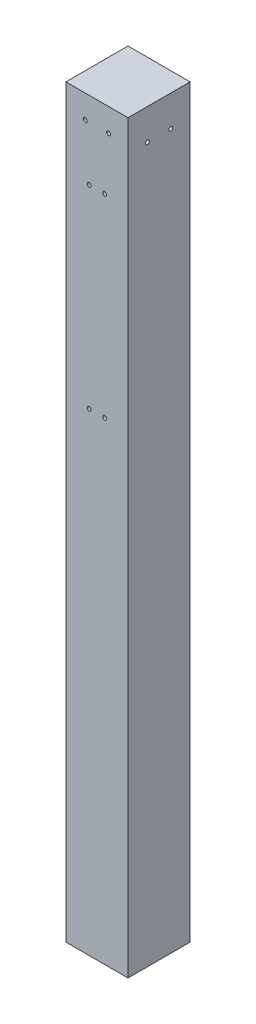
SolidWorks part; units mm, degrees
material "Pine"
ref_plane "Frontal Plane" through (0, 0, 0) normal (0, 0, 1) x (1, 0, 0)
ref_plane "Horizontal Plane" through (0, 0, 0) normal (0, 1, 0) x (1, 0, 0)
ref_plane "Profile Plane" through (0, 0, 0) normal (1, 0, 0) x (0, 0, -1)
sketch "Sketch1" plane through (0, 0, 0) normal (0, 1, 0) x (1, 0, 0)
  line L1 (50.8, -50.8) -> (-50.8, -50.8)
  line L2 (50.8, -50.8) -> (50.8, 50.8)
  line L3 (50.8, 50.8) -> (-50.8, 50.8)
  line L4 (-50.8, -50.8) -> (-50.8, 50.8)
  line L5 (50.8, -50.8) -> (-50.8, 50.8) construction
  line L6 (50.8, 50.8) -> (-50.8, -50.8) construction
  point P0 (0, 0)
  dimension "D1" = 101.6
  dimension "D2" = 101.6
extrude "Boss-Extrude1" add sketch "Sketch1" along normal mid plane 1219.2
sketch "Sketch2" plane through (50.8, 0, 0) normal (1, 0, 0) x (0, 0, -1)
  line L0 (-50.8, 609.6) -> (50.8, 609.6) construction
  line L1 (-50.8, 609.6) -> (-50.8, -609.6) construction
  line L2 (50.8, 609.6) -> (50.8, -609.6) construction
  circle A0 centre (-19.05, 558.8) radius 3.175
  circle A1 centre (19.05, 558.8) radius 3.175
  dimension "D2" = 6.35
  dimension "D1" = 50.8
  dimension "D3" = 31.75
  dimension "D4" = 31.75
extrude "Cut-Extrude1" cut sketch "Sketch2" against normal through all
sketch "Sketch3" plane through (0, 0, 50.8) normal (0, 0, 1) x (1, 0, 0)
  line L0 (-50.8, 609.6) -> (50.8, 609.6) construction
  line L1 (-50.8, 609.6) -> (-50.8, -609.6) construction
  line L2 (50.8, 609.6) -> (50.8, -609.6) construction
  circle A0 centre (-19.05, 571.5) radius 3.175
  circle A1 centre (19.05, 571.5) radius 3.175
  dimension "D1" = 6.35
  dimension "D2" = 38.1
  dimension "D3" = 31.75
  dimension "D4" = 31.75
extrude "Cut-Extrude2" cut sketch "Sketch3" against normal through all
sketch "Sketch4" plane through (0, 0, 50.8) normal (0, 0, 1) x (1, 0, 0)
  line L0 (-50.8, 609.6) -> (50.8, 609.6) construction
  line L1 (-50.8, 609.6) -> (-50.8, -609.6) construction
  line L2 (50.8, 609.6) -> (50.8, -609.6) construction
  circle A0 centre (-12.7, 482.6) radius 3.175
  circle A1 centre (12.7, 482.6) radius 3.175
  circle A2 centre (-12.7, 165.1) radius 3.175
  circle A3 centre (12.7, 165.1) radius 3.175
  dimension "D1" = 6.35
  dimension "D2" = 127
  dimension "D3" = 38.1
  dimension "D4" = 38.1
  dimension "D5" = 317.5
extrude "Cut-Extrude3" cut sketch "Sketch4" against normal blind 44.45
